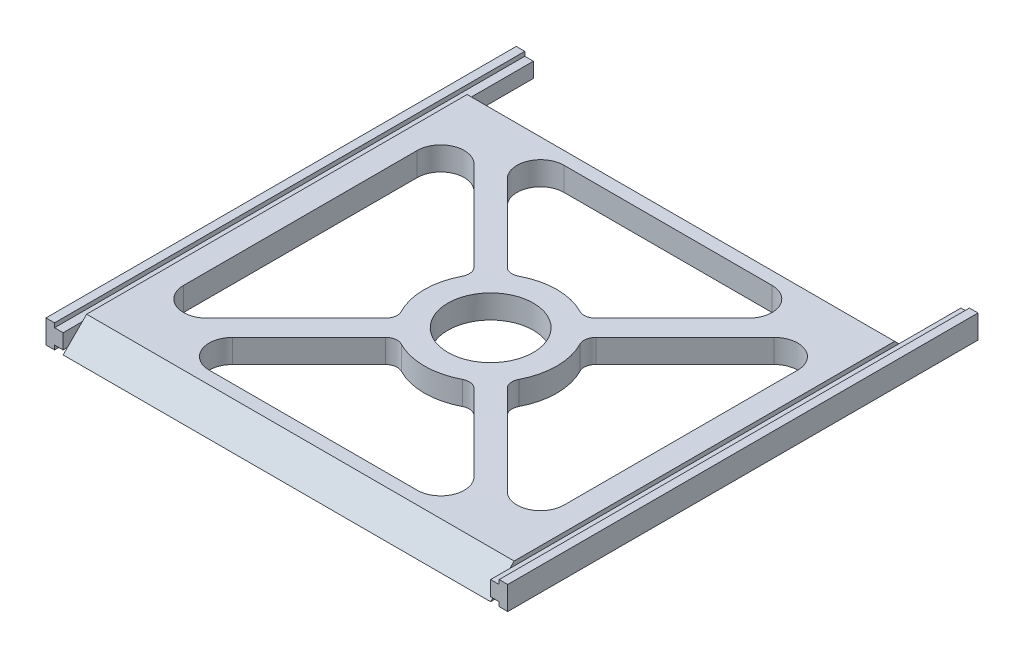
SolidWorks part; units mm, degrees
material "Alumina"
ref_plane "Front Plane" through (0, 0, 0) normal (0, 0, 1) x (1, 0, 0)
ref_plane "Top Plane" through (0, 0, 0) normal (0, 1, 0) x (1, 0, 0)
ref_plane "Right Plane" through (0, 0, 0) normal (1, 0, 0) x (0, 0, -1)
sketch "Sketch1" plane through (0, 0, 0) normal (0, 1, 0) x (1, 0, 0)
  line L0 (0, 110) -> (4, 110)
  line L1 (0, 0) -> (108, 0)
  line L2 (0, 0) -> (0, 110)
  line L4 (108, 0) -> (108, 110)
  line L5 (4, 110) -> (4, 100)
  line L6 (4, 100) -> (104, 100)
  line L7 (104, 100) -> (104, 110)
  line L8 (104, 110) -> (108, 110)
  dimension "D1" = 110
  dimension "D2" = 108
  dimension "D3" = 4
  dimension "D4" = 4
  dimension "D5" = 10
  dimension "D6" = 10
extrude "Boss-Extrude1" add sketch "Sketch1" along normal blind 5.5
sketch "Sketch4" plane through (0, 0, -110) normal (0, 0, -1) x (-1, 0, 0)
  line L1 (-4, 0) -> (-2, 0)
  line L2 (-4, 0) -> (-4, 1)
  line L3 (-4, 1) -> (-2, 1)
  line L4 (-2, 0) -> (-2, 1)
  line L5 (-4, 5.5) -> (-2, 5.5)
  line L6 (-4, 5.5) -> (-4, 4.5)
  line L7 (-4, 4.5) -> (-2, 4.5)
  line L8 (-2, 5.5) -> (-2, 4.5)
  line L9 (-104, 5.5) -> (-106, 5.5)
  line L10 (-104, 5.5) -> (-104, 4.5)
  line L11 (-104, 4.5) -> (-106, 4.5)
  line L12 (-106, 5.5) -> (-106, 4.5)
  line L13 (-104, 0) -> (-106, 0)
  line L14 (-104, 0) -> (-104, 1)
  line L15 (-104, 1) -> (-106, 1)
  line L16 (-106, 0) -> (-106, 1)
  dimension "D1" = 2
  dimension "D2" = 2
  dimension "D3" = 2
  dimension "D4" = 2
  dimension "D5" = 1
  dimension "D6" = 1
  dimension "D7" = 1
  dimension "D8" = 1
extrude "Cut-Extrude2" cut sketch "Sketch4" against normal blind 110
sketch "Sketch5" plane through (0, 5.5, 0) normal (0, 1, 0) x (1, 0, 0)
  line L0 (0, 0) -> (54, 0) construction
  line L1 (4, 0) -> (104, 0) construction
  line L2 (54, 0) -> (54, 100) construction
  line L3 (104, 100) -> (4, 100) construction
  line L4 (54, 50) -> (22.1802, 18.1802) construction
  line L5 (54, 50) -> (22.1802, 81.8198) construction
  line L6 (41.2692, 41.1583) -> (9.5, 9.3891)
  line L7 (9.5, 9.3891) -> (9.5, 90.6109)
  line L8 (9.5, 90.6109) -> (41.2692, 58.8417)
  line L9 (4, 0) -> (4, 100) construction
  line L14 (98.5, 90.6109) -> (98.5, 9.3891)
  line L15 (66.7308, 58.8417) -> (98.5, 90.6109)
  line L16 (98.5, 9.3891) -> (66.7308, 41.1583)
  line L20 (13.3891, 94.5) -> (94.6109, 94.5) [skipped]
  line L21 (45.1583, 62.7308) -> (13.3891, 94.5) [skipped]
  line L22 (94.6109, 94.5) -> (62.8417, 62.7308) [skipped]
  line L23 (62.8417, 37.2692) -> (94.6109, 5.5) [skipped]
  line L24 (13.3891, 5.5) -> (45.1583, 37.2692) [skipped]
  line L25 (94.6109, 5.5) -> (13.3891, 5.5) [skipped]
  line L26 (45.1583, 62.7308) -> (16.3891, 91.5)
  line L27 (16.3891, 91.5) -> (91.6109, 91.5)
  line L28 (91.6109, 91.5) -> (62.8417, 62.7308)
  line L29 (54, 50) -> (64, 50) construction
  line L30 (16.3891, 8.5) -> (91.6109, 8.5)
  line L31 (91.6109, 8.5) -> (62.8417, 37.2692)
  line L32 (45.1583, 37.2692) -> (16.3891, 8.5)
  circle A0 centre (54, 50) radius 10
  arc A1 (41.2692, 58.8417) -> (41.2692, 41.1583) centre (54, 50) ccw
  arc A3 (66.7308, 41.1583) -> (66.7308, 58.8417) centre (54, 50) ccw
  arc A5 (62.8417, 62.7308) -> (45.1583, 62.7308) centre (54, 50) ccw [skipped]
  arc A6 (45.1583, 37.2692) -> (62.8417, 37.2692) centre (54, 50) ccw [skipped]
  arc A7 (45.1583, 62.7308) -> (62.8417, 62.7308) centre (54, 50) cw
  arc A8 (45.1583, 37.2692) -> (62.8417, 37.2692) centre (54, 50) ccw
  point P34 (54, 50)
  dimension "D1" = 20
  dimension "D7" = 15.5
  dimension "D9" = 15.5
  dimension "D2" = 45
  dimension "D3" = 45
  dimension "D4" = 2.75
  dimension "D5" = 2.75
  dimension "D6" = 5.5
  dimension "D10" = 8.5
  dimension "D11" = 2.75
  dimension "D12" = 5.5
  dimension "D13" = 10
  dimension "D14" = 45
  dimension "D15" = 45
  dimension "D8" = 4
extrude "Cut-Extrude3" cut sketch "Sketch5" against normal blind 110
sketch "Sketch6" plane through (108, 0, 0) normal (1, 0, 0) x (0, 0, -1)
  line L0 (0, 0) -> (5.5, 5.5)
  line L1 (0, 5.5) -> (110, 5.5) construction
  line L2 (5.5, 5.5) -> (0, 5.5)
  line L3 (0, 5.5) -> (0, 0)
  line L4 (100, 5.5) -> (100, 0)
  line L9 (0, 0) -> (110, 0) construction
  line L10 (100, 0) -> (94.5, 5.5)
  line L11 (94.5, 5.5) -> (100, 5.5)
  line L12 (110, 5.5) -> (110, 0) construction
  dimension "D1" = 45
  dimension "D2" = 10
  dimension "D3" = 45
extrude "Cut-Extrude4" cut sketch "Sketch6" against normal blind 100 from offset 4 offset against normal yes
fillet "Fillet3" radius 5.5 8 edges at (91.6109, 2.75, -8.5) (98.5, 2.75, -9.3891) (98.5, 2.75, -90.6109) (91.6109, 2.75, -91.5) (16.3891, 2.75, -91.5) (9.5, 2.75, -90.6109) (9.5, 2.75, -9.3891) (16.3891, 2.75, -8.5)
fillet "Fillet4" radius 2.75 8 edges at (66.7308, 2.75, -41.1583) (66.7308, 2.75, -58.8417) (62.8417, 2.75, -62.7308) (45.1583, 2.75, -62.7308) (41.2692, 2.75, -41.1583) (41.2692, 2.75, -58.8417) (62.8417, 2.75, -37.2692) (45.1583, 2.75, -37.2692)
